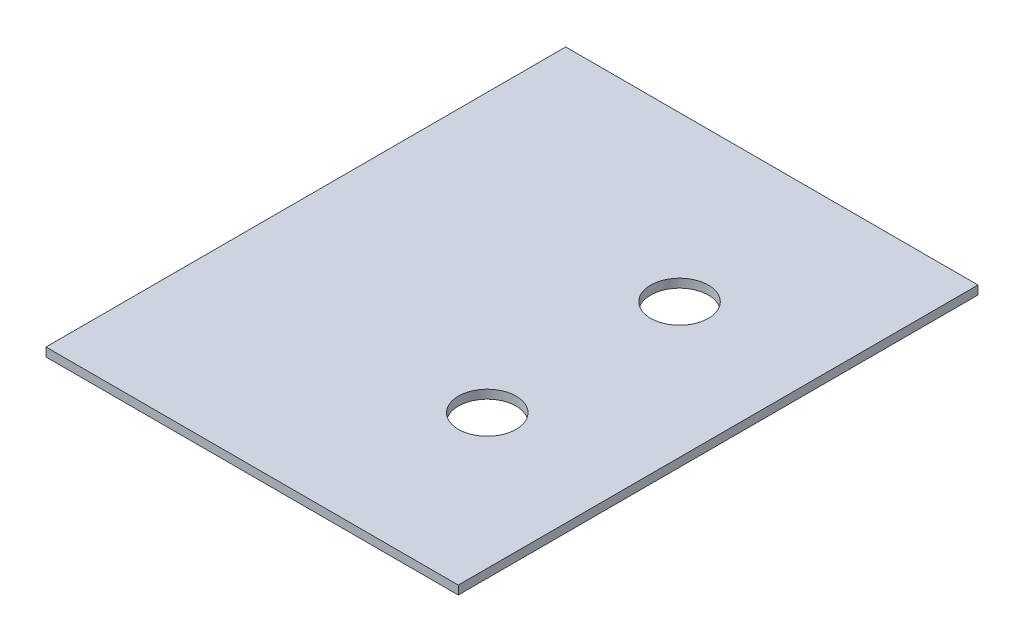
SolidWorks part; units mm, degrees
ref_plane "Front" through (0, 0, 0) normal (0, 0, 1) x (1, 0, 0)
ref_plane "Top" through (0, 0, 0) normal (0, 1, 0) x (1, 0, 0)
ref_plane "Right" through (0, 0, 0) normal (1, 0, 0) x (0, 0, -1)
sketch "Sketch1" plane through (0, 0, 0) normal (0, 1, 0) x (1, 0, 0)
  line L1 (-11.9, 15) -> (11.9, 15)
  line L2 (-11.9, 15) -> (-11.9, -15)
  line L3 (-11.9, -15) -> (11.9, -15)
  line L4 (11.9, 15) -> (11.9, -15)
  line L5 (-11.9, 15) -> (11.9, -15) construction
  line L6 (-11.9, -15) -> (11.9, 15) construction
  point P0 (0, 0)
  dimension "D1" = 23.8
  dimension "D2" = 30
extrude "Boss-Extrude1" add sketch "Sketch1" along normal blind 0.5
sketch "Sketch2" plane through (0, 0.5, 0) normal (0, 1, 0) x (1, 0, 0)
  circle A0 centre (4.1214, 5.5494) radius 1.665
  circle A1 centre (4.1214, -5.55) radius 1.665
  dimension "D1" = 3.33
extrude "Cut-Extrude1" cut sketch "Sketch2" against normal up to next
